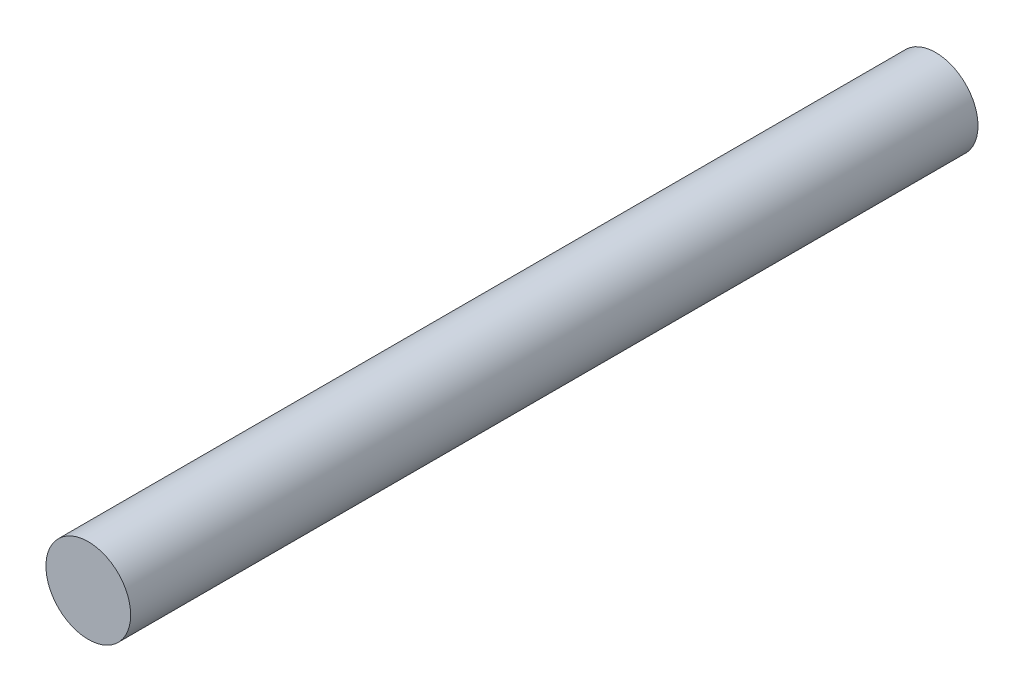
SolidWorks part; units mm, degrees
ref_plane "Front Plane" through (0, 0, 0) normal (0, 0, 1) x (1, 0, 0)
ref_plane "Top Plane" through (0, 0, 0) normal (0, 1, 0) x (1, 0, 0)
ref_plane "Right Plane" through (0, 0, 0) normal (1, 0, 0) x (0, 0, -1)
sketch "Sketch1" plane through (0, 0, 0) normal (0, 0, 1) x (1, 0, 0)
  circle A0 centre (0, 0) radius 10
  dimension "D1" = 20
extrude "Boss-Extrude1" add sketch "Sketch1" along normal mid plane 200
